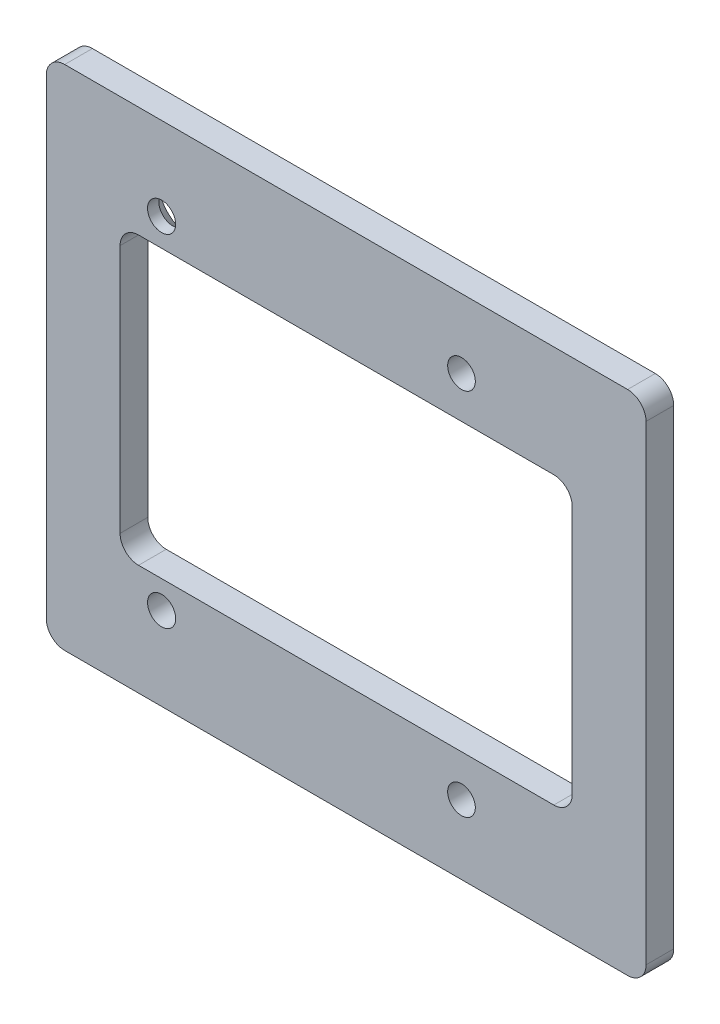
SolidWorks part; units mm, degrees
material "Thornel Mat VMA"
ref_plane "前视基准面" through (0, 0, 0) normal (0, 0, 1) x (1, 0, 0)
ref_plane "上视基准面" through (0, 0, 0) normal (0, 1, 0) x (1, 0, 0)
ref_plane "右视基准面" through (0, 0, 0) normal (1, 0, 0) x (0, 0, -1)
sketch "草图1" plane through (0, 0, 0) normal (0, 0, 1) x (1, 0, 0)
  line L1 (-32.5, -27.5) -> (32.5, -27.5)
  line L2 (-32.5, -27.5) -> (-32.5, 27.5)
  line L3 (-32.5, 27.5) -> (32.5, 27.5)
  line L4 (32.5, -27.5) -> (32.5, 27.5)
  line L5 (0, 27.5) -> (0, -27.5) construction
  line L6 (-32.5, 0) -> (32.5, 0) construction
  point P0 (0, 0)
  dimension "D1" = 65
  dimension "D2" = 55
extrude "凸台-拉伸1" add sketch "草图1" along normal blind 3
fillet "圆角1" radius 2 4 edges at (32.5, -27.5, 1.5) (-32.5, -27.5, 1.5) (-32.5, 27.5, 1.5) (32.5, 27.5, 1.5)
sketch "草图2" plane through (0, 0, 0) normal (0, 0, -1) x (-1, 0, 0)
  line L0 (20, -27.5) -> (20, -18.5) construction
  line L1 (30.5, -27.5) -> (-30.5, -27.5) construction
  line L2 (32.5, 25.5) -> (32.5, -25.5) construction
  line L3 (20, -18.5) -> (20, 18.5) construction
  line L4 (0, 0) -> (20, 0) construction
  circle A0 centre (20, -18.5) radius 1.525
  circle A1 centre (20, 18.5) radius 1.525
  dimension "D4" = 3.05
  dimension "D1" = 12.5
  dimension "D3" = 37
extrude "切除-拉伸1" cut sketch "草图2" against normal blind 6
hole_wizard "M3 十字槽沉头木螺钉的锥形沉头孔1" positions "草图3" profile "草图4" countersink size "M3" standard "GB"
sketch "草图3" plane through (0, 0, 0) normal (0, 0, -1) x (-1, 0, 0)
  point P0 (20, 18.5)
sketch "草图4" plane through (-20, 18.5, 0) normal (1, 0, 0) x (0, 1, 0)
  line L0 (0, 0) -> (0, 8.1513)
  line L1 (0, 8.1513) -> (1.5, 7.25)
  line L2 (1.5, 7.25) -> (1.5, 1.8)
  line L3 (1.5, 1.8) -> (3.3, 0)
  line L5 (3.3, 0) -> (0, 0)
  line L6 (-1.5, 1.8) -> (-3.3, 0) construction
  line L10 (0, 8.1513) -> (-1.5, 7.25) construction
  line L11 (0, -6.35) -> (0, 107.95) construction
  dimension "孔直径" = 3
  dimension "孔深度" = 7.25
  dimension "近端锥形沉头孔直径" = 6.6
  dimension "近端锥形沉头孔角度" = 90
  dimension "导头角度" = 118
sketch "草图5" [suppressed] plane through (0, 0, 0) normal (0, 0, -1) x (-1, 0, 0)
  line L0 (-20, -27.5) -> (-20, -18.5) construction
  line L1 (-20, 0) -> (0, 0) construction
  line L3 (30.5, -27.5) -> (-30.5, -27.5) construction
  line L4 (-20, -18.5) -> (-20, 18.5) construction
  line L5 (-32.5, -25.5) -> (-32.5, 25.5) construction
  circle A0 centre (-20, -18.5) radius 1.525
  circle A1 centre (-20, 18.5) radius 1.525
  dimension "D3" = 3.05
  dimension "D1" = 12.5
  dimension "D4" = 37
extrude "切除-拉伸2" [suppressed] cut sketch "草图5" against normal blind 6
hole_wizard "M3 十字槽沉头木螺钉的锥形沉头孔2" [suppressed] positions "草图6" profile "草图7" countersink size "M3" standard "GB"
sketch "草图6" plane through (0, 0, 0) normal (0, 0, -1) x (-1, 0, 0)
  point P0 (-20, 18.5)
sketch "草图7" plane through (20, 18.5, 0) normal (1, 0, 0) x (0, 1, 0)
  line L0 (0, 0) -> (0, 8.1513)
  line L1 (0, 8.1513) -> (1.5, 7.25)
  line L2 (1.5, 7.25) -> (1.5, 1.8)
  line L3 (1.5, 1.8) -> (3.3, 0)
  line L5 (3.3, 0) -> (0, 0)
  line L6 (-1.5, 1.8) -> (-3.3, 0) construction
  line L10 (0, 8.1513) -> (-1.5, 7.25) construction
  line L11 (0, -6.35) -> (0, 107.95) construction
  dimension "孔直径" = 3
  dimension "孔深度" = 7.25
  dimension "近端锥形沉头孔直径" = 6.6
  dimension "近端锥形沉头孔角度" = 90
  dimension "导头角度" = 118
sketch "草图8" [suppressed] plane through (0, 0, 0) normal (0, 0, -1) x (-1, 0, 0)
  line L0 (30.5, 27.5) -> (44.5, 27.5)
  line L1 (44.5, 27.5) -> (44.5, -27.5)
  line L2 (44.5, -27.5) -> (30.5, -27.5)
  line L3 (30.5, -27.5) -> (-30.5, -27.5) construction
  line L4 (32.5, 25.5) -> (32.5, -25.5) construction
  line L5 (30.5, 27.5) -> (30.5, -27.5)
  dimension "D1" = 12
extrude "凸台-拉伸2" [suppressed] add sketch "草图8" against normal up to surface (6 mm away)
sketch "草图9" plane through (0, 0, 0) normal (0, 0, -1) x (-1, 0, 0)
  circle A0 centre (-12.5, 20) radius 1.5 construction
  circle A1 centre (-12.5, -20) radius 1.5 construction
  circle A2 centre (-12.5, 20) radius 1.5
  circle A3 centre (-12.5, -20) radius 1.5
extrude "切除-拉伸3" cut sketch "草图9" against normal blind 10
sketch "草图10" [suppressed] plane through (0, 0, 0) normal (0, 0, -1) x (-1, 0, 0)
  circle A0 centre (12.5, 20) radius 1.5 construction
  circle A1 centre (12.5, -20) radius 1.5 construction
  circle A2 centre (12.5, 20) radius 1.5
  circle A3 centre (12.5, -20) radius 1.5
extrude "切除-拉伸4" [suppressed] cut sketch "草图10" against normal blind 10
sketch "草图11" [suppressed] plane through (0, 557.4607, 0) normal (0, 1, 0) x (1, 0, 0)
  circle A0 centre (57.5, 31) radius 1.525 construction
  circle A1 centre (307.5, 31) radius 1.525 construction
  circle A2 centre (57.5, 31) radius 1.525
  circle A3 centre (307.5, 31) radius 1.525
sketch "草图12" [suppressed] plane through (0, 0, 0) normal (0, 0, -1) x (-1, 0, 0)
  line L0 (-24.5, 13.5) -> (-15, 13.5)
  line L1 (-15, 13.5) -> (-15, 15)
  line L2 (-15, 15) -> (24.5, 15)
  line L3 (24.5, 15) -> (24.5, -15)
  line L4 (24.5, -15) -> (-15, -15)
  line L5 (-15, -15) -> (-15, -13.5)
  line L6 (-15, -13.5) -> (-24.5, -13.5)
  line L7 (-24.5, -13.5) -> (-24.5, 13.5)
  line L8 (0, 0) -> (24.5, 0) construction
  line L9 (0, 0) -> (-24.5, 0) construction
  line L10 (-32.5, -25.5) -> (-32.5, 25.5) construction
  line L11 (32.5, 25.5) -> (32.5, -25.5) construction
  circle A0 centre (12.5, 20) radius 1.5 construction
  circle A1 centre (-20, 18.5) radius 1.525 construction
  dimension "D1" = 5
  dimension "D2" = 5
  dimension "D3" = 5
  dimension "D4" = 8
  dimension "D5" = 8
extrude "切除-拉伸7" [suppressed] cut sketch "草图12" against normal blind 10
fillet "圆角2" [suppressed] radius 2
fillet "圆角3" [suppressed] radius 2
sketch "草图13" plane through (0, 0, 0) normal (0, 0, -1) x (-1, 0, 0)
  line L0 (32.5, 25.5) -> (32.5, -25.5) construction
  line L1 (-24.5, -15.5) -> (24.5, -15.5)
  line L2 (-24.5, -15.5) -> (-24.5, 15.5)
  line L3 (-24.5, 15.5) -> (24.5, 15.5)
  line L4 (24.5, -15.5) -> (24.5, 15.5)
  line L5 (0, 15.5) -> (0, -15.5) construction
  line L6 (-24.5, 0) -> (24.5, 0) construction
  circle A0 centre (20, -18.5) radius 1.525 construction
  point P0 (0, 0)
  dimension "D1" = 3
  dimension "D2" = 8
extrude "切除-拉伸8" cut sketch "草图13" against normal blind 10
fillet "圆角5" radius 2 4 edges at (-24.5, -15.5, 1.5) (-24.5, 15.5, 1.5) (24.5, -15.5, 1.5) (24.5, 15.5, 1.5)
